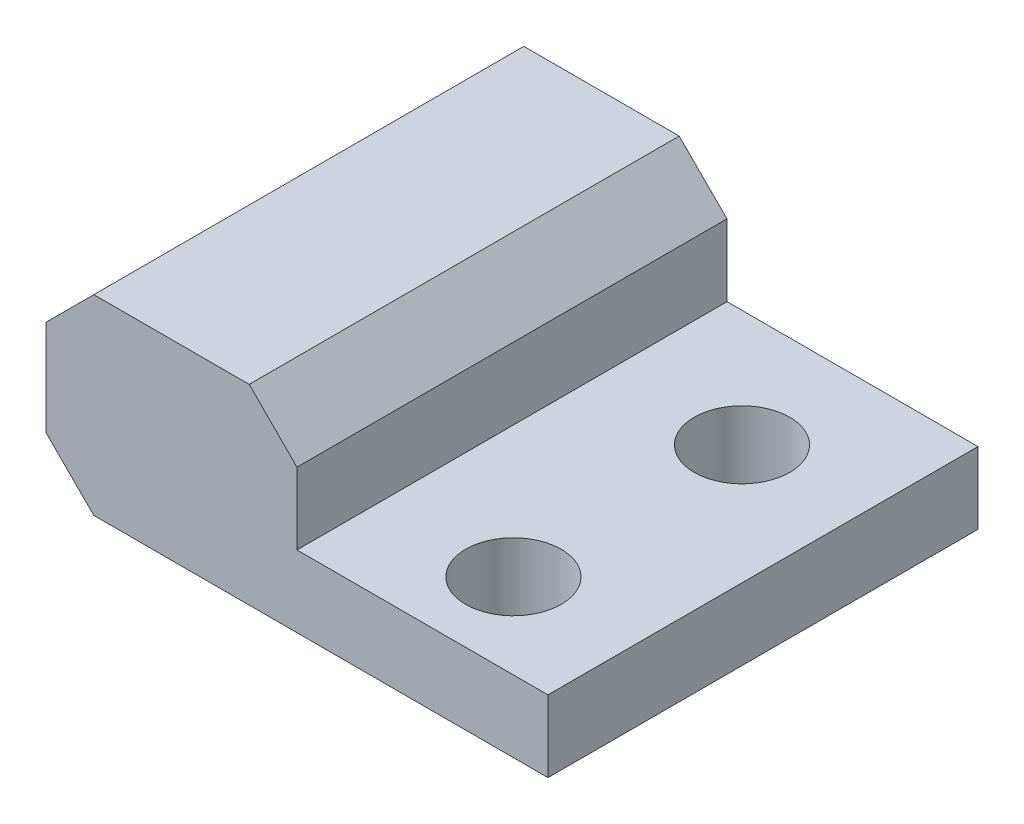
SolidWorks part; units mm, degrees
ref_plane "Спереди" through (0, 0, 0) normal (0, 0, 1) x (1, 0, 0)
ref_plane "Сверху" through (0, 0, 0) normal (0, 1, 0) x (1, 0, 0)
ref_plane "Справа" through (0, 0, 0) normal (1, 0, 0) x (0, 0, -1)
sketch "Эскиз1" plane through (0, 0, 0) normal (0, 1, 0) x (1, 0, 0)
  line L0 (10, -17.9909) -> (0, -17.9909) construction
  line L1 (-11, 0) -> (10, 0)
  line L2 (-11, 0) -> (-11, -17.9909)
  line L3 (-11, -17.9909) -> (10, -17.9909)
  line L4 (10, 0) -> (10, -17.9909)
extrude "Вытянуть1" add sketch "Эскиз1" along normal blind 8
sketch "Эскиз2" plane through (0, 8, 0) normal (0, 1, 0) x (1, 0, 0)
  line L0 (-11, -17.9909) -> (10, -17.9909) construction
  line L1 (-0.5, -17.9909) -> (10, -17.9909)
  line L2 (-0.5, -17.9909) -> (-0.5, 0.0035)
  line L3 (-0.5, 0.0035) -> (10, 0.0035)
  line L4 (10, -17.9909) -> (10, 0.0035)
extrude "Вырез-Вытянуть1" cut sketch "Эскиз2" against normal blind 5
sketch "Эскиз3" plane through (0, 3, 0) normal (0, 1, 0) x (1, 0, 0)
  circle A0 centre (5, -14.4361) radius 2
  circle A1 centre (5, -4.8736) radius 2
extrude "Вырез-Вытянуть2" cut sketch "Эскиз3" against normal through all
sketch "Эскиз4" plane through (0, 0, 0) normal (0, 0, 1) x (1, 0, 0)
  circle A0 centre (-5.5, 4.0907) radius 2.6
extrude "Вырез-Вытянуть3" cut sketch "Эскиз4" along normal blind 15
chamfer "Фаска1" distance 2 angle 45 3 edges at (-0.5, 8, 8.9954) (-11, 0, 8.9954) (-11, 8, 8.9954)
